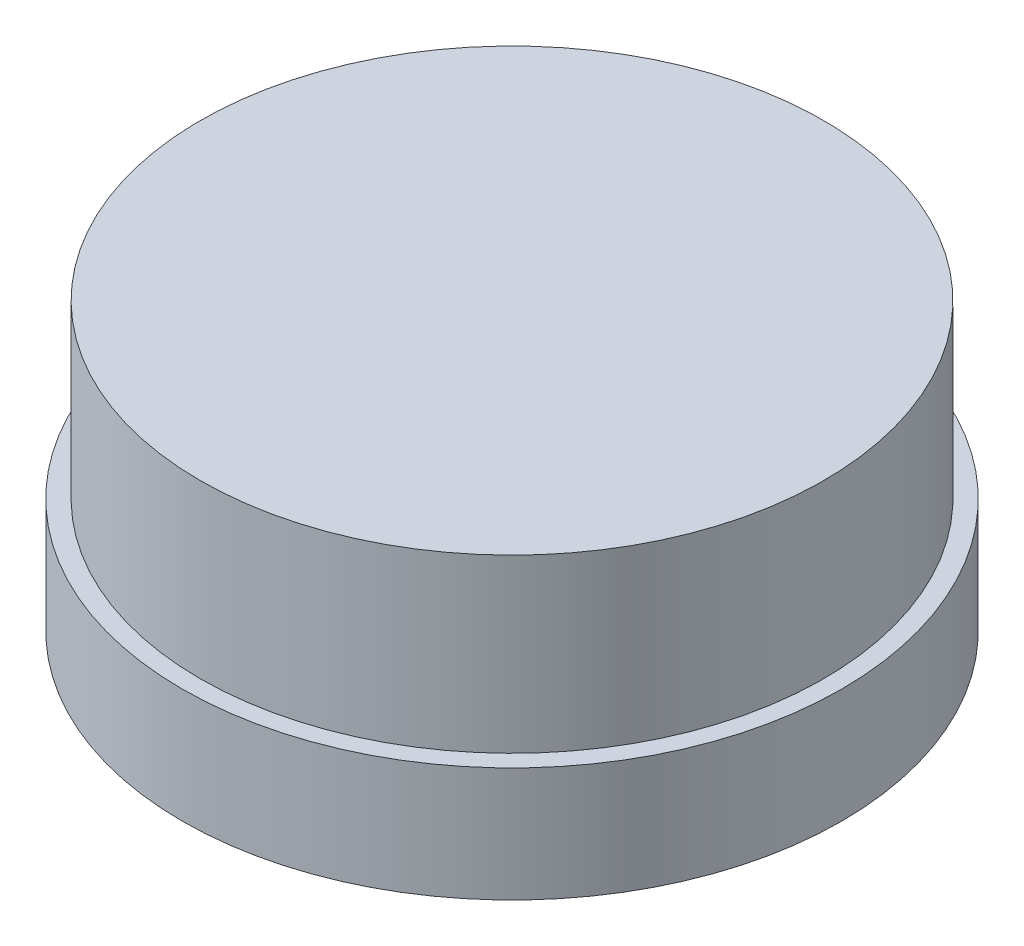
SolidWorks part; units mm, degrees
ref_plane "前视基准面" through (0, 0, 0) normal (0, 0, 1) x (1, 0, 0)
ref_plane "上视基准面" through (0, 0, 0) normal (0, 1, 0) x (1, 0, 0)
ref_plane "右视基准面" through (0, 0, 0) normal (1, 0, 0) x (0, 0, -1)
sketch "草图1" plane through (0, 0, 0) normal (0, 1, 0) x (1, 0, 0)
  circle A0 centre (0, 0) radius 16.35
  dimension "D1" = 32.7
extrude "凸台-拉伸1" add sketch "草图1" along normal blind 9
sketch "草图2" plane through (0, 0, 0) normal (0, -1, 0) x (1, 0, 0)
  circle A0 centre (0, 0) radius 17.29
  dimension "D1" = 34.58
extrude "凸台-拉伸2" add sketch "草图2" along normal blind 6
